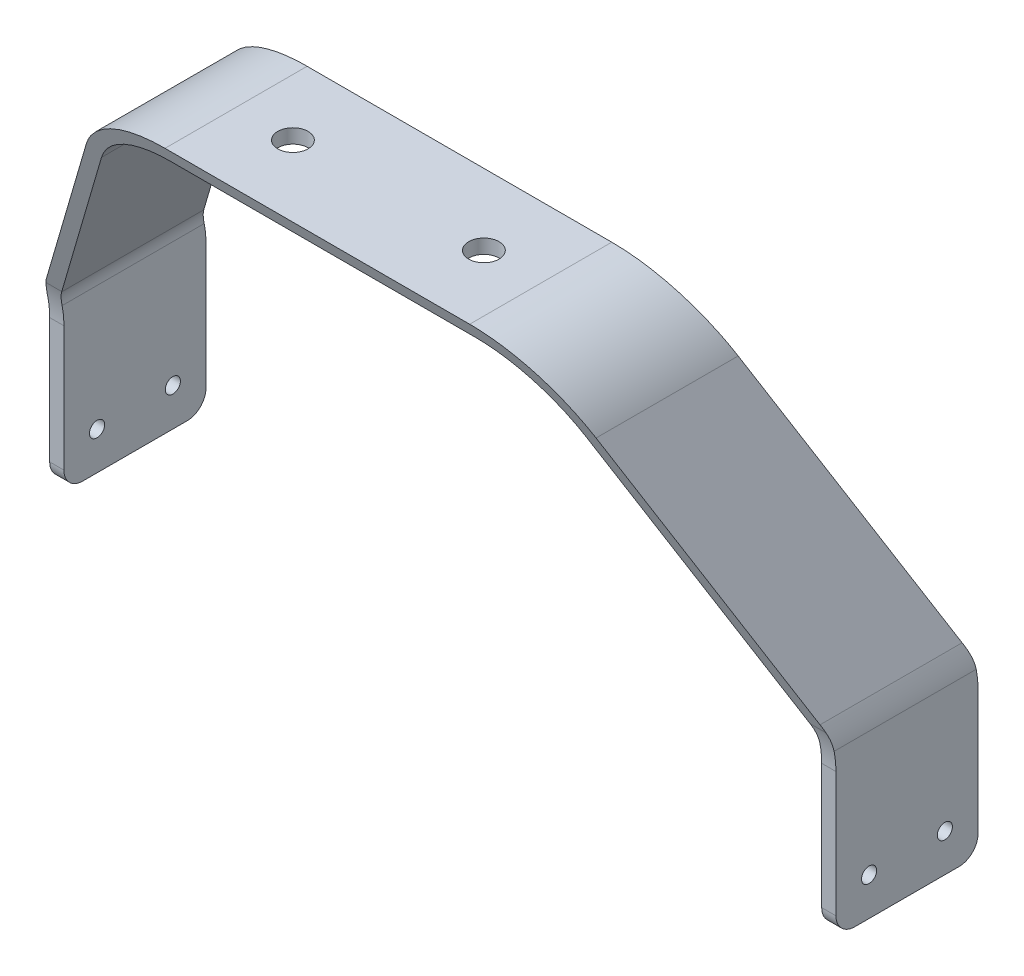
SolidWorks part; units mm, degrees
ref_plane "Front Plane" through (0, 0, 0) normal (0, 0, 1) x (1, 0, 0)
ref_plane "Top Plane" through (0, 0, 0) normal (0, 1, 0) x (1, 0, 0)
ref_plane "Right Plane" through (0, 0, 0) normal (1, 0, 0) x (0, 0, -1)
sketch "Sketch4" plane through (0, 0, -249) normal (0, 0, -1) x (-1, 0, 0)
  line L0 (-83, 0) -> (-83, 34.267)
  line L1 (-81.6603, 39.267) -> (-53.8129, 87.5)
  line L2 (-32.1623, 100) -> (0, 100)
  line L3 (0, 100) -> (0, -90.398) construction
  line L5 (-80, 0) -> (-80, 34.267)
  line L6 (-79.0622, 37.767) -> (-51.2148, 86)
  line L7 (-32.1623, 97) -> (0, 97)
  line L8 (-83, 0) -> (-80, 0)
  line L9 (32.1623, 100) -> (0, 100)
  line L10 (32.1623, 97) -> (0, 97)
  line L11 (83, 0) -> (80, 0)
  line L12 (79.0622, 37.767) -> (51.2148, 86)
  line L13 (80, 0) -> (80, 34.267)
  line L14 (81.6603, 39.267) -> (53.8129, 87.5)
  line L15 (83, 0) -> (83, 34.267)
  arc A0 (-53.8129, 87.5) -> (-32.1623, 100) centre (-32.1623, 75) cw
  arc A1 (-83, 34.267) -> (-81.6603, 39.267) centre (-73, 34.267) cw
  arc A2 (-80, 34.267) -> (-79.0622, 37.767) centre (-73, 34.267) cw
  arc A3 (-51.2148, 86) -> (-32.1623, 97) centre (-32.1623, 75) cw
  arc A4 (51.2148, 86) -> (32.1623, 97) centre (32.1623, 75) ccw
  arc A5 (80, 34.267) -> (79.0622, 37.767) centre (73, 34.267) ccw
  arc A6 (83, 34.267) -> (81.6603, 39.267) centre (73, 34.267) ccw
  arc A7 (53.8129, 87.5) -> (32.1623, 100) centre (32.1623, 75) ccw
extrude "Boss-Extrude4" add sketch "Sketch4" against normal blind 20 and the other way blind 40
sketch "Sketch5" plane through (83, 0, 0) normal (1, 0, 0) x (0, 0, -1)
  line L0 (229, 100) -> (254.0377, 37.864)
  line L1 (289, 34.267) -> (229, 34.267) construction
  line L2 (255.4871, 30.389) -> (255.4871, 0)
  line L3 (252, 0) -> (390, 0) construction
  line L4 (255.4871, 0) -> (285.4871, 0)
  line L5 (285.4871, 0) -> (285.4871, 30.389)
  line L6 (229, 100) -> (259, 100)
  line L7 (289, 100) -> (229, 100) construction
  line L8 (259, 100) -> (284.0377, 37.864)
  arc A0 (285.4871, 30.389) -> (284.0377, 37.864) centre (265.4871, 30.389) ccw
  arc A1 (254.0377, 37.864) -> (255.4871, 30.389) centre (235.4871, 30.389) cw
  point P17 (255.4871, 34.267)
  dimension "D3" = 20
  dimension "D1" = 30
  dimension "D2" = 30
extrude "Cut-Extrude1" cut sketch "Sketch5" against normal through all flip side to cut
sketch "Sketch6" plane through (83, 0, 0) normal (1, 0, 0) x (0, 0, -1)
  line L0 (255.4871, 30.389) -> (255.4871, 0) construction
  line L1 (285.4871, 0) -> (285.4871, 30.389) construction
  line L2 (285.4871, 0) -> (255.4871, 0) construction
  circle A0 centre (262.4871, 8) radius 1.6
  circle A1 centre (278.4871, 8) radius 1.6
  dimension "D1" = 7
  dimension "D2" = 7
  dimension "D3" = 8
  dimension "D4" = 8
extrude "Cut-Extrude2" cut sketch "Sketch6" against normal through all
fillet "Fillet1" radius 4 4 edges at (81.5, 0, -285.4871) (81.5, 0, -255.4871) (-81.5, 0, -255.4871) (-81.5, 0, -285.4871)
sketch "Sketch7" plane through (0, 100, 0) normal (0, 1, 0) x (1, 0, 0)
  line L0 (-32.1623, 244) -> (32.1623, 244) construction
  line L1 (-32.1623, 259) -> (-32.1623, 229) construction
  line L2 (32.1623, 259) -> (32.1623, 229) construction
  circle A0 centre (-20.1623, 244) radius 3.2
  circle A1 centre (20.1623, 244) radius 3.2
  dimension "D1" = 12
  dimension "D2" = 12
extrude "Cut-Extrude3" cut sketch "Sketch7" against normal blind 3
